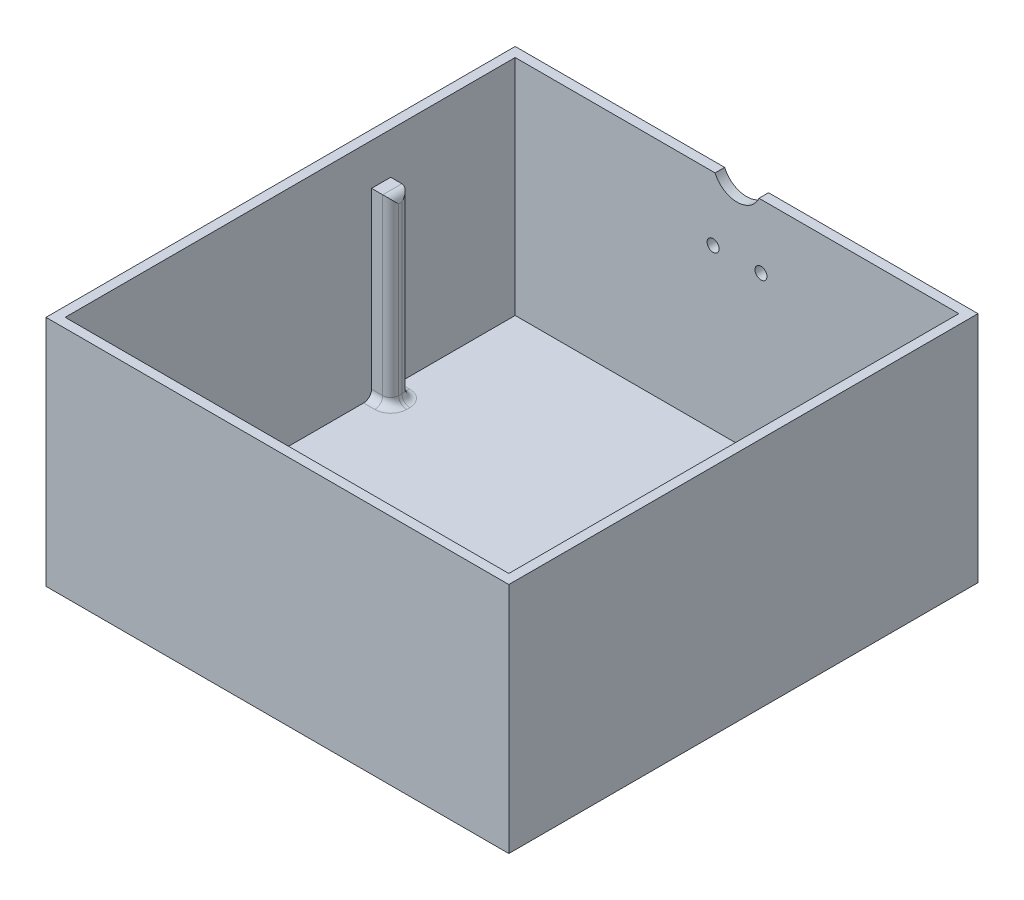
SolidWorks part; units mm, degrees
ref_plane "Front Plane" through (0, 0, 0) normal (0, 0, 1) x (1, 0, 0)
ref_plane "Top Plane" through (0, 0, 0) normal (0, 1, 0) x (1, 0, 0)
ref_plane "Right Plane" through (0, 0, 0) normal (1, 0, 0) x (0, 0, -1)
sketch "Sketch1" plane through (0, 0, 0) normal (0, 1, 0) x (1, 0, 0)
  line L1 (0, 0) -> (116, 0)
  line L2 (0, 0) -> (0, -117.6)
  line L3 (0, -117.6) -> (116, -117.6)
  line L4 (116, 0) -> (116, -117.6)
  dimension "D1" = 117.6
  dimension "D2" = 116
extrude "Boss-Extrude1" add sketch "Sketch1" along normal blind 2.4
sketch "Sketch2" plane through (0, 2.4, 0) normal (0, 1, 0) x (1, 0, 0)
  line L1 (113.6, -115.2) -> (113.6, -2.4)
  line L2 (116, -117.6) -> (0, -117.6)
  line L3 (116, -117.6) -> (116, 0)
  line L4 (116, 0) -> (0, 0)
  line L5 (0, -117.6) -> (0, 0)
  line L6 (113.6, -2.4) -> (2.4, -2.4)
  line L7 (2.4, -115.2) -> (2.4, -2.4)
  line L8 (113.6, -115.2) -> (2.4, -115.2)
  dimension "D1" = 2.4
extrude "Boss-Extrude2" add sketch "Sketch2" along normal blind 56
sketch "Sketch3" plane through (0, 0, 0) normal (0, 0, -1) x (-1, 0, 0)
  line L1 (-116, 58.4) -> (0, 58.4) construction
  circle A0 centre (-64, 42.4) radius 1.5
  circle A1 centre (-52, 42.4) radius 1.5
  point P6 (-58, 58.4)
  dimension "D1" = 3
  dimension "D2" = 3
  dimension "D3" = 12
  dimension "D4" = 16
  dimension "D5" = 16
  dimension "D6" = 6
extrude "Cut-Extrude1" cut sketch "Sketch3" against normal blind 10
sketch "Sketch7" plane through (0, 2.4, 0) normal (0, 1, 0) x (1, 0, 0)
  line L1 (2.4, -2.4) -> (2.4, -115.2) construction
  line L2 (2.4, -115.2) -> (7.2, -115.2)
  line L3 (2.4, -115.2) -> (2.4, -110.4)
  line L4 (2.4, -110.4) -> (7.2, -110.4)
  line L5 (7.2, -115.2) -> (7.2, -110.4)
  line L6 (2.4, -38.4) -> (7.2, -38.4)
  line L7 (2.4, -38.4) -> (2.4, -33.6)
  line L8 (2.4, -33.6) -> (7.2, -33.6)
  line L9 (7.2, -38.4) -> (7.2, -33.6)
  line L10 (113.6, -115.2) -> (113.6, -2.4) construction
  line L11 (113.6, -115.2) -> (108.8, -115.2)
  line L12 (113.6, -115.2) -> (113.6, -110.4)
  line L14 (113.6, -110.4) -> (108.8, -110.4)
  line L15 (108.8, -115.2) -> (108.8, -110.4)
  line L16 (113.6, -38.4) -> (108.8, -38.4)
  line L17 (113.6, -38.4) -> (113.6, -33.6)
  line L18 (113.6, -33.6) -> (108.8, -33.6)
  line L19 (108.8, -38.4) -> (108.8, -33.6)
  dimension "D1" = 4.8
  dimension "D2" = 4.8
  dimension "D3" = 4.8
  dimension "D4" = 4.8
  dimension "D5" = 4.8
  dimension "D6" = 4.8
  dimension "D7" = 4.8
  dimension "D8" = 4.8
  dimension "D9" = 72
  dimension "D10" = 72
extrude "Boss-Extrude4" add sketch "Sketch7" along normal blind 45.6
fillet "Fillet2" radius 2 18 edges at (4.8, 2.4, 38.4) (4.8, 2.4, 33.6) (111.2, 2.4, 33.6) (111.2, 2.4, 38.4) (7.2, 25.2, 38.4) (7.2, 48, 36) (7.2, 25.2, 33.6) (7.2, 2.4, 36) (108.8, 25.2, 33.6) (108.8, 48, 36) (108.8, 25.2, 38.4) (108.8, 2.4, 36) (7.2, 25.2, 110.4) (108.8, 25.2, 110.4) (4.8, 2.4, 110.4) (7.2, 2.4, 112.8) (108.8, 2.4, 112.8) (111.2, 2.4, 110.4)
sketch "Sketch8" plane through (0, 0, 0) normal (0, 0, -1) x (-1, 0, 0)
  circle A0 centre (-58, 60.8) radius 6
  circle A1 centre (-64, 42.4) radius 1.5 construction
  circle A2 centre (-64, 42.4) radius 1.5 construction
  dimension "D3" = 12
  dimension "D1" = 18.4
  dimension "D2" = 6
extrude "Cut-Extrude2" cut sketch "Sketch8" against normal blind 10
equation "\"D1@Sketch1\"=0.8*147"
equation "\"D2@Sketch1\"=0.8*145"
equation "\"D1@Boss-Extrude4\"=0.8*57"
equation "\"D5@Sketch3\"=\"D4@Sketch3\""
